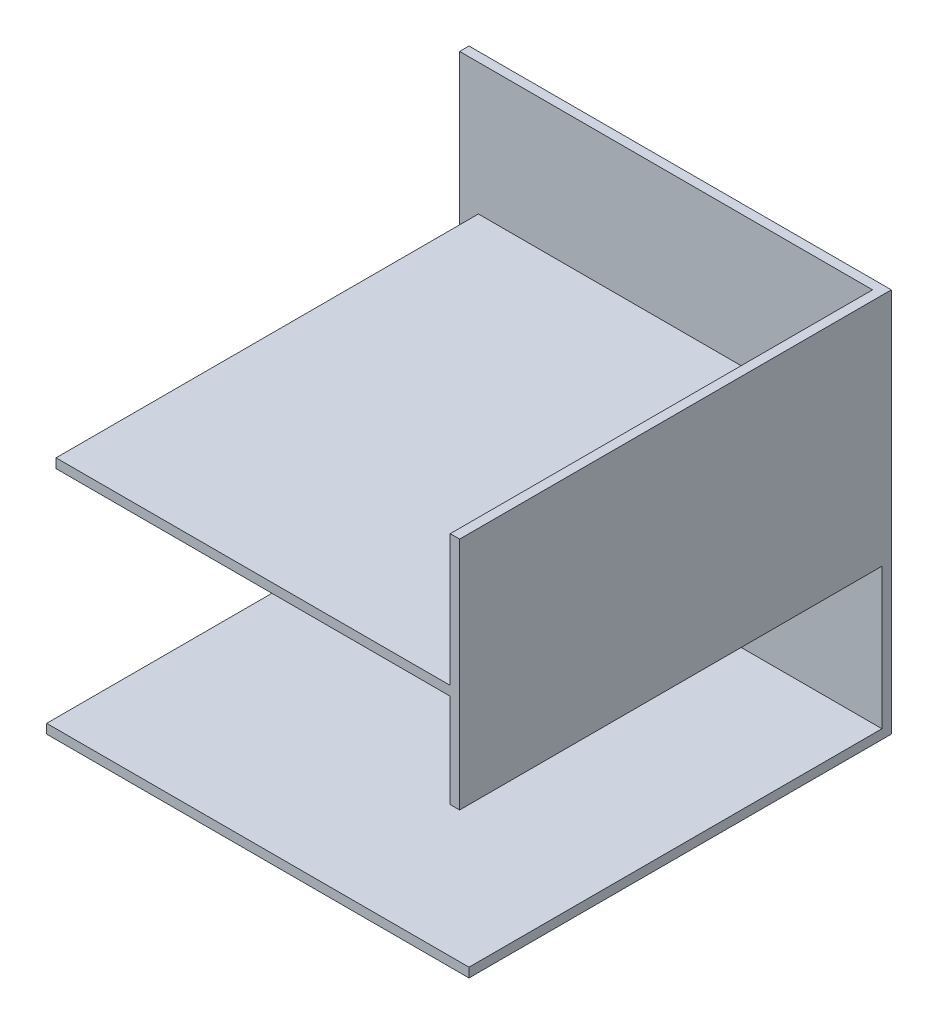
SolidWorks part; units mm, degrees
ref_plane "Front Plane" through (0, 0, 0) normal (0, 0, 1) x (1, 0, 0)
ref_plane "Top Plane" through (0, 0, 0) normal (0, 1, 0) x (1, 0, 0)
ref_plane "Right Plane" through (0, 0, 0) normal (1, 0, 0) x (0, 0, -1)
sketch "Sketch1" plane through (0, 0, 0) normal (0, 0, 1) x (1, 0, 0)
  line L1 (-22.9393, 4.7533) -> (427.0607, 4.7533)
  line L2 (-22.9393, 4.7533) -> (-22.9393, -5.2467)
  line L3 (-22.9393, -5.2467) -> (427.0607, -5.2467)
  line L4 (427.0607, 4.7533) -> (427.0607, -5.2467)
  point P4 (427.0607, -0.2467)
  dimension "D1" = 450
  dimension "D2" = 10
extrude "Boss-Extrude1" add sketch "Sketch1" along normal blind 450
sketch "Sketch2" plane through (0, 4.7533, 0) normal (0, 1, 0) x (1, 0, 0)
  line L0 (-22.9393, -450) -> (-22.9393, 0) construction
  line L1 (-22.9393, -10) -> (427.0607, -10)
  line L2 (-22.9393, -10) -> (-22.9393, 0)
  line L3 (-22.9393, 0) -> (427.0607, 0)
  line L4 (427.0607, -10) -> (427.0607, 0)
  line L5 (427.0607, 0) -> (-22.9393, 0) construction
  line L6 (427.0607, -450) -> (427.0607, 0) construction
  dimension "D1" = 0
  dimension "D2" = 0
  dimension "D3" = 0
  dimension "D4" = 10
extrude "Boss-Extrude2" add sketch "Sketch2" along normal blind 400
sketch "Sketch3" plane through (0, 0, 10) normal (0, 0, 1) x (1, 0, 0)
  line L0 (-22.9393, 404.7533) -> (427.0607, 404.7533) construction
  line L1 (417.0607, 404.7533) -> (427.0607, 404.7533)
  line L2 (417.0607, 404.7533) -> (417.0607, 154.7533)
  line L3 (417.0607, 154.7533) -> (427.0607, 154.7533)
  line L4 (427.0607, 404.7533) -> (427.0607, 154.7533)
  line L5 (427.0607, 404.7533) -> (427.0607, 4.7533) construction
  line L6 (-22.9393, 4.7533) -> (427.0607, 4.7533) construction
  dimension "D1" = 0
  dimension "D2" = 0
  dimension "D3" = 150
  dimension "D4" = 10
extrude "Boss-Extrude3" add sketch "Sketch3" along normal blind 450
sketch "Sketch4" plane through (0, 0, 10) normal (0, 0, 1) x (1, 0, 0)
  line L1 (-2.9393, 264.7533) -> (417.0607, 264.7533)
  line L2 (-2.9393, 264.7533) -> (-2.9393, 254.7533)
  line L3 (-2.9393, 254.7533) -> (417.0607, 254.7533)
  line L4 (417.0607, 264.7533) -> (417.0607, 254.7533)
  line L5 (-22.9393, 4.7533) -> (427.0607, 4.7533) construction
  line L6 (417.0607, 404.7533) -> (417.0607, 154.7533) construction
  line L7 (-22.9393, 404.7533) -> (-22.9393, 4.7533) construction
  point P4 (417.0607, 259.7533)
  dimension "D1" = 250
  dimension "D2" = 10
  dimension "D3" = 0
  dimension "D4" = 20
extrude "Boss-Extrude4" add sketch "Sketch4" along normal blind 450
